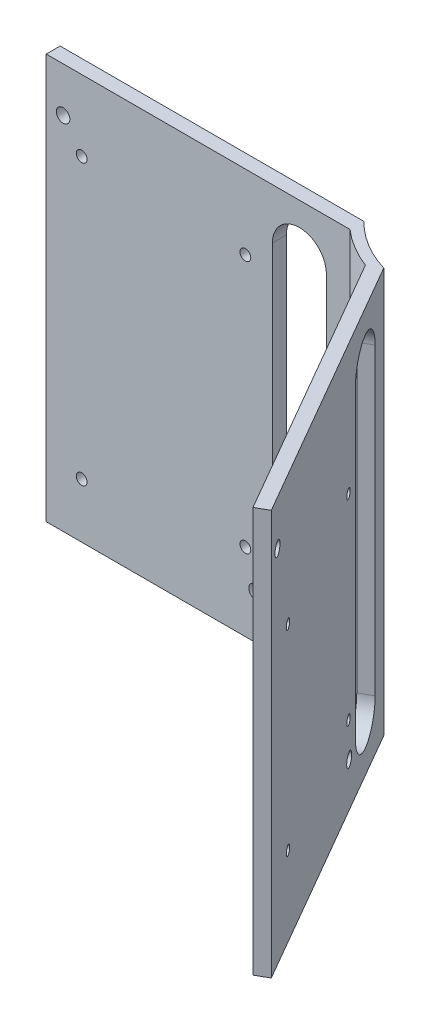
SolidWorks part; units mm, degrees
ref_plane "Plan de face" through (0, 0, 0) normal (0, 0, 1) x (1, 0, 0)
ref_plane "Plan de dessus" through (0, 0, 0) normal (0, 1, 0) x (1, 0, 0)
ref_plane "Plan de droite" through (0, 0, 0) normal (1, 0, 0) x (0, 0, -1)
sketch "Esquisse3" plane through (0, 0, 0) normal (0, 1, 0) x (1, 0, 0)
  line L0 (-150.1573, 0) -> (189.6273, 0) construction
  line L1 (-83.8395, -145.9242) -> (87.7229, 151.2306) construction
  line L2 (-78.0725, 135.2255) -> (117.7517, -203.9519) construction
  line L3 (-125, 131.2995) -> (-125, -153.5705) construction
  line L4 (-25, -24.4949) -> (-115, -24.4949)
  line L6 (-21.2883, 25.5051) -> (-23.9685, 25.5051)
  line L7 (-115, -24.4949) -> (-115, 25.5051)
  line L8 (-25, -24.4949) -> (-115, 25.5051) construction
  line L9 (-21.2883, 25.5051) -> (-115, -24.4949) construction
  line L10 (-23.9685, 25.5051) -> (-115, 25.5051)
  line L11 (34.0723, 8.0048) -> (79.5881, 86.8404)
  line L12 (36.2868, 111.8404) -> (79.5881, 86.8404)
  line L13 (-8.7132, 33.8981) -> (36.2868, 111.8404)
  line L14 (-10.1038, -33.5099) -> (35.4119, -112.3455)
  line L15 (78.7132, -87.3455) -> (35.4119, -112.3455)
  line L16 (33.7132, -9.4032) -> (78.7132, -87.3455)
  line L17 (-23.9685, 25.5051) -> (-25, -24.4949)
  line L18 (-8.7132, 33.8981) -> (34.0723, 8.0048)
  line L19 (-10.1038, -33.5099) -> (33.7132, -9.4032)
  line L20 (-25, -28.6182) -> (-115, -28.6182)
  line L21 (-115, -28.6182) -> (-115, -24.4949)
  line L22 (-13.5526, -35.5011) -> (31.9631, -114.3367)
  line L23 (31.9631, -114.3367) -> (35.4119, -112.3455)
  circle A0 centre (0, 0) radius 125
  circle A1 centre (0, 0) radius 35
  circle A2 centre (0, 0) radius 125
  circle A3 centre (0, 0) radius 125
  circle A4 centre (0, 0) radius 38
  point P9 (-69.0908, 0)
  point P32 (0, 0)
  dimension "D1" = 250
  dimension "D4" = 70
  dimension "D2" = 120
  dimension "D3" = 120
  dimension "D5" = 10
  dimension "D6" = 50
  dimension "D7" = 90
  dimension "D9" = 3
  dimension "D8" = 3
extrude "Boss.-Extru.1" add sketch "Esquisse3" along normal blind 120 contours A4 L4 L21 L20 | L4 A4 L14 A1 | A4 L22 L23 L14
sketch "Esquisse4" plane through (0, 0, 28.6182) normal (0, 0, 1) x (1, 0, 0)
  line L0 (-40, 120) -> (-40, 0) construction
  line L1 (-25, 120) -> (-115, 120) construction
  line L2 (-25, 0) -> (-115, 0) construction
  line L3 (-48, 105) -> (-48, 15)
  line L4 (-25, 120) -> (-25, 0) construction
  line L5 (-115, 60) -> (-20.315, 60) construction
  line L6 (-115, 120) -> (-115, 0) construction
  line L7 (-32, 105) -> (-32, 15)
  arc A0 (-48, 15) -> (-32, 15) centre (-40, 15) ccw
  arc A1 (-48, 105) -> (-32, 105) centre (-40, 105) cw
  dimension "D1" = 8
  dimension "D2" = 15
  dimension "D3" = 45
  dimension "D4" = 45
extrude "Enlèv. mat.-Extru.1" cut sketch "Esquisse4" against normal through all
sketch "Esquisse5" plane through (-25.5369, 0, 14.7437) normal (-0.866, 0, 0.5) x (0.5, 0, 0.866)
  line L0 (38.9685, 120) -> (38.9685, 0) construction
  line L1 (23.9685, 120) -> (115, 120) construction
  line L2 (46.9685, 105) -> (46.9685, 15)
  line L3 (38.9685, 60) -> (127.8483, 60) construction
  line L4 (115, 120) -> (115, 0) construction
  line L5 (23.9685, 120) -> (23.9685, 0) construction
  line L6 (30.9685, 105) -> (30.9685, 15)
  arc A0 (46.9685, 15) -> (30.9685, 15) centre (38.9685, 15) cw
  arc A1 (46.9685, 105) -> (30.9685, 105) centre (38.9685, 105) ccw
  point P14 (115, 60)
  dimension "D1" = 8
  dimension "D2" = 45
  dimension "D3" = 45
  dimension "D4" = 15
extrude "Enlèv. mat.-Extru.2" cut sketch "Esquisse5" against normal through all
sketch "Esquisse6" plane through (0, 0, 28.6182) normal (0, 0, 1) x (1, 0, 0)
  circle A0 centre (-110, 106.75) radius 2 construction
  circle A1 centre (-110, 106.75) radius 2
sketch "Esquisse7" plane through (-25.5369, 0, 14.7437) normal (-0.866, 0, 0.5) x (0.5, 0, 0.866)
  circle A0 centre (110, 106.75) radius 2 construction
  circle A1 centre (110, 106.75) radius 2
extrude "Enlèv. mat.-Extru.3" cut sketch "Esquisse6" against normal through all
extrude "Enlèv. mat.-Extru.4" cut sketch "Esquisse7" against normal through all
ref_plane "Plan1" through (-57.6, 23, 30.2182) normal (0, -1, 0) x (-1, 0, 0)
sketch "Esquisse9" plane through (0, 0, 28.6182) normal (0, 0, 1) x (1, 0, 0)
  arc A0 (-54.4, 23) -> (-57.6, 23) centre (-56, 23) ccw construction
  arc A1 (-106.1, 16.2) -> (-102.9, 16.2) centre (-104.5, 16.2) ccw construction
  arc A2 (-102.9, 16.2) -> (-106.1, 16.2) centre (-104.5, 16.2) ccw construction
  arc A3 (-57.6, 98) -> (-54.4, 98) centre (-56, 98) ccw construction
  arc A4 (-54.4, 98) -> (-57.6, 98) centre (-56, 98) ccw construction
  arc A5 (-106.1, 99) -> (-102.9, 99) centre (-104.5, 99) ccw construction
  arc A6 (-102.9, 99) -> (-106.1, 99) centre (-104.5, 99) ccw construction
  arc A7 (-54.4, 23) -> (-57.6, 23) centre (-56, 23) ccw
  arc A8 (-106.1, 16.2) -> (-102.9, 16.2) centre (-104.5, 16.2) ccw
  arc A9 (-102.9, 16.2) -> (-106.1, 16.2) centre (-104.5, 16.2) ccw
  arc A10 (-57.6, 98) -> (-54.4, 98) centre (-56, 98) ccw
  arc A11 (-54.4, 98) -> (-57.6, 98) centre (-56, 98) ccw
  arc A12 (-106.1, 99) -> (-102.9, 99) centre (-104.5, 99) ccw
  arc A13 (-102.9, 99) -> (-106.1, 99) centre (-104.5, 99) ccw
  arc A14 (-57.6, 23) -> (-54.4, 23) centre (-56, 23) ccw construction
  arc A15 (-57.6, 23) -> (-54.4, 23) centre (-56, 23) ccw
sketch "Esquisse10" plane through (-25.5369, 0, 14.7437) normal (-0.866, 0, 0.5) x (0.5, 0, 0.866)
  circle A0 centre (101.5, 23.5) radius 1.3645 construction
  circle A1 centre (52.5, 23.5) radius 1.3645 construction
  circle A2 centre (52.5, 81.5855) radius 1.3645 construction
  circle A3 centre (101.5, 81.5855) radius 1.3645 construction
  circle A4 centre (101.5, 23.5) radius 1.3645
  circle A5 centre (52.5, 23.5) radius 1.3645
  circle A6 centre (52.5, 81.5855) radius 1.3645
  circle A7 centre (101.5, 81.5855) radius 1.3645
extrude "Enlèv. mat.-Extru.5" cut sketch "Esquisse10" against normal through all
extrude "Enlèv. mat.-Extru.6" cut sketch "Esquisse9" against normal through all
sketch "Esquisse11" plane through (0, 0, 28.6182) normal (0, 0, 1) x (1, 0, 0)
  circle A0 centre (-53, 13) radius 2 construction
  circle A1 centre (-53, 13) radius 2
sketch "Esquisse12" plane through (-25.5369, 0, 14.7437) normal (-0.866, 0, 0.5) x (0.5, 0, 0.866)
  circle A0 centre (51.9685, 13) radius 2 construction
  circle A1 centre (51.9685, 13) radius 2
extrude "Enlèv. mat.-Extru.7" cut sketch "Esquisse11" against normal through all
extrude "Enlèv. mat.-Extru.8" cut sketch "Esquisse12" against normal through all
